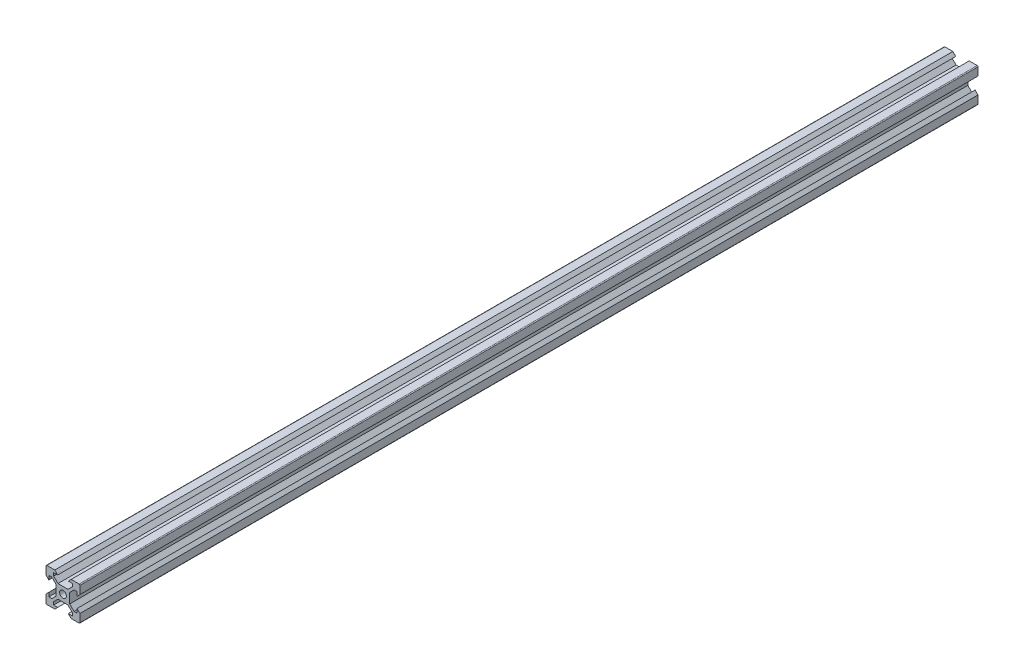
SolidWorks part; units mm, degrees
ref_plane "Alzado" through (0, 0, 0) normal (0, 0, 1) x (1, 0, 0)
ref_plane "Planta" through (0, 0, 0) normal (0, 1, 0) x (1, 0, 0)
ref_plane "Vista lateral" through (0, 0, 0) normal (1, 0, 0) x (0, 0, -1)
sketch "Croquis1" plane through (0, 0, 0) normal (0, 0, 1) x (1, 0, 0)
  line L0 (-4.825, 10) -> (-3.125, 8.3)
  line L1 (-9.5, -10) -> (-4.825, -10)
  line L2 (-10, -9.5) -> (-10, -4.825)
  line L3 (-9.5, 10) -> (-4.825, 10)
  line L4 (10, -9.5) -> (10, -4.825)
  line L5 (-10, -10) -> (10, 10) construction
  line L6 (-10, 10) -> (10, -10) construction
  line L7 (-2.9393, -4) -> (2.9393, -4)
  line L8 (-4, -2.9393) -> (-4, 2.9393)
  line L9 (-2.9393, 4) -> (2.9393, 4)
  line L10 (4, -2.9393) -> (4, 2.9393)
  line L11 (-4, -4) -> (4, 4) construction
  line L12 (-4, 4) -> (4, -4) construction
  line L13 (0, 10) -> (0, -10) construction
  line L14 (-3.125, 8.3) -> (-5.5, 8.3)
  line L15 (-6.5607, 5.5) -> (-4, 2.9393)
  line L16 (-5.5, 6.5607) -> (-2.9393, 4)
  line L17 (-9.4697, 10.5303) -> (10.5303, -9.4697) construction
  line L18 (-10, 4.825) -> (-8.3, 3.125)
  line L19 (-5.5, 8.3) -> (-5.5, 6.5607)
  line L20 (-8.3, 3.125) -> (-8.3, 5.5)
  line L21 (-8.3, 5.5) -> (-6.5607, 5.5)
  line L22 (10, 4.825) -> (8.3, 3.125)
  line L23 (8.3, 3.125) -> (8.3, 5.5)
  line L24 (8.3, 5.5) -> (6.5607, 5.5)
  line L25 (6.5607, 5.5) -> (4, 2.9393)
  line L26 (5.5, 6.5607) -> (2.9393, 4)
  line L27 (5.5, 8.3) -> (5.5, 6.5607)
  line L28 (3.125, 8.3) -> (5.5, 8.3)
  line L29 (4.825, 10) -> (3.125, 8.3)
  line L30 (4.825, -10) -> (3.125, -8.3)
  line L31 (3.125, -8.3) -> (5.5, -8.3)
  line L32 (5.5, -8.3) -> (5.5, -6.5607)
  line L33 (5.5, -6.5607) -> (2.9393, -4)
  line L34 (6.5607, -5.5) -> (4, -2.9393)
  line L35 (8.3, -5.5) -> (6.5607, -5.5)
  line L36 (8.3, -3.125) -> (8.3, -5.5)
  line L37 (10, -4.825) -> (8.3, -3.125)
  line L38 (-10, -4.825) -> (-8.3, -3.125)
  line L39 (-8.3, -3.125) -> (-8.3, -5.5)
  line L40 (-8.3, -5.5) -> (-6.5607, -5.5)
  line L41 (-6.5607, -5.5) -> (-4, -2.9393)
  line L42 (-5.5, -6.5607) -> (-2.9393, -4)
  line L43 (-5.5, -8.3) -> (-5.5, -6.5607)
  line L44 (-3.125, -8.3) -> (-5.5, -8.3)
  line L45 (-4.825, -10) -> (-3.125, -8.3)
  line L46 (-10, 4.825) -> (-10, 9.5)
  line L47 (4.825, 10) -> (9.5, 10)
  line L48 (10, 4.825) -> (10, 9.5)
  line L49 (4.825, -10) -> (9.5, -10)
  circle A0 centre (0, 0) radius 2
  arc A1 (-10, 9.5) -> (-9.5, 10) centre (-9.5, 9.5) cw
  arc A2 (9.5, 10) -> (10, 9.5) centre (9.5, 9.5) cw
  arc A3 (9.5, -10) -> (10, -9.5) centre (9.5, -9.5) ccw
  arc A4 (-9.5, -10) -> (-10, -9.5) centre (-9.5, -9.5) cw
  point P0 (0, 0)
  point P59 (0, 0)
  dimension "D2" = 4
  dimension "D9" = 0.5
  dimension "D1" = 20
  dimension "D3" = 8
  dimension "D4" = 3.125
  dimension "D5" = 5.5
  dimension "D6" = 4.3
  dimension "D7" = 4
  dimension "D8" = 0.75
extrude "Saliente-Extruir2" add sketch "Croquis1" along normal mid plane 530
